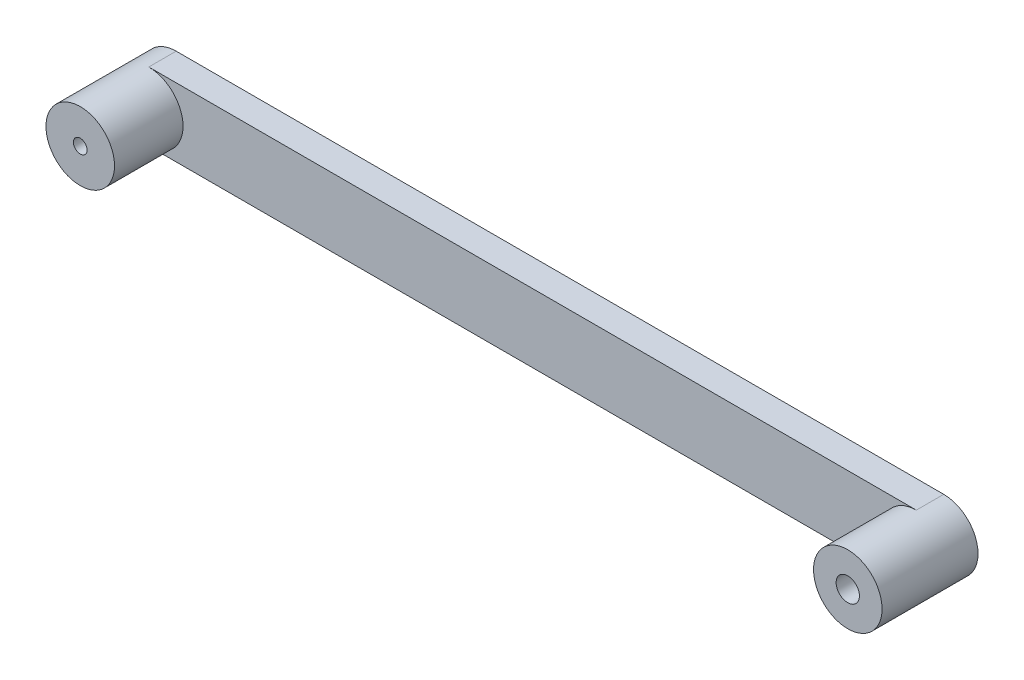
SolidWorks part; units mm, degrees
ref_plane "Plano frontal" through (0, 0, 0) normal (0, 0, 1) x (1, 0, 0)
ref_plane "Plano superior" through (0, 0, 0) normal (0, 1, 0) x (1, 0, 0)
ref_plane "Plano direito" through (0, 0, 0) normal (1, 0, 0) x (0, 0, -1)
sketch "Esboço1" plane through (0, 0, 0) normal (0, 0, 1) x (1, 0, 0)
  line L0 (-28, 0) -> (28, 0) construction
  line L1 (-28, 2.5) -> (28, 2.5)
  line L2 (-28, -2.5) -> (28, -2.5)
  arc A0 (-28, 2.5) -> (-28, -2.5) centre (-28, 0) ccw
  arc A1 (28, -2.5) -> (28, 2.5) centre (28, 0) ccw
  point P2 (0, 0)
  dimension "D2" = 5
  dimension "D1" = 56
extrude "Ressalto-extrusão1" add sketch "Esboço1" along normal blind 2
sketch "Esboço3" plane through (0, 0, 2) normal (0, 0, 1) x (1, 0, 0)
  circle A0 centre (28, 0) radius 2.5
  arc A2 (28, -2.5) -> (28, 2.5) centre (28, 0) ccw construction
extrude "Ressalto-extrusão2" add sketch "Esboço3" along normal blind 5
sketch "Esboço5" plane through (0, 0, 2) normal (0, 0, 1) x (1, 0, 0)
  circle A0 centre (-28, 0) radius 2.5
  arc A1 (-28, 2.5) -> (-28, -2.5) centre (-28, 0) ccw construction
extrude "Ressalto-extrusão3" add sketch "Esboço5" along normal blind 5
sketch "Esboço2" plane through (0, 0, 7) normal (0, 0, 1) x (1, 0, 0)
  circle A0 centre (-28, 0) radius 0.5
  arc A1 (-28, -2.5) -> (-28, 2.5) centre (-28, 0) ccw construction
  dimension "D1" = 1
extrude "Corte-extrusão1" cut sketch "Esboço2" against normal through all
sketch "Esboço4" plane through (0, 0, 7) normal (0, 0, 1) x (1, 0, 0)
  circle A0 centre (28, 0) radius 0.85
  circle A1 centre (28, 0) radius 2.5 construction
  dimension "D1" = 1.7
extrude "Corte-extrusão2" cut sketch "Esboço4" against normal through all
